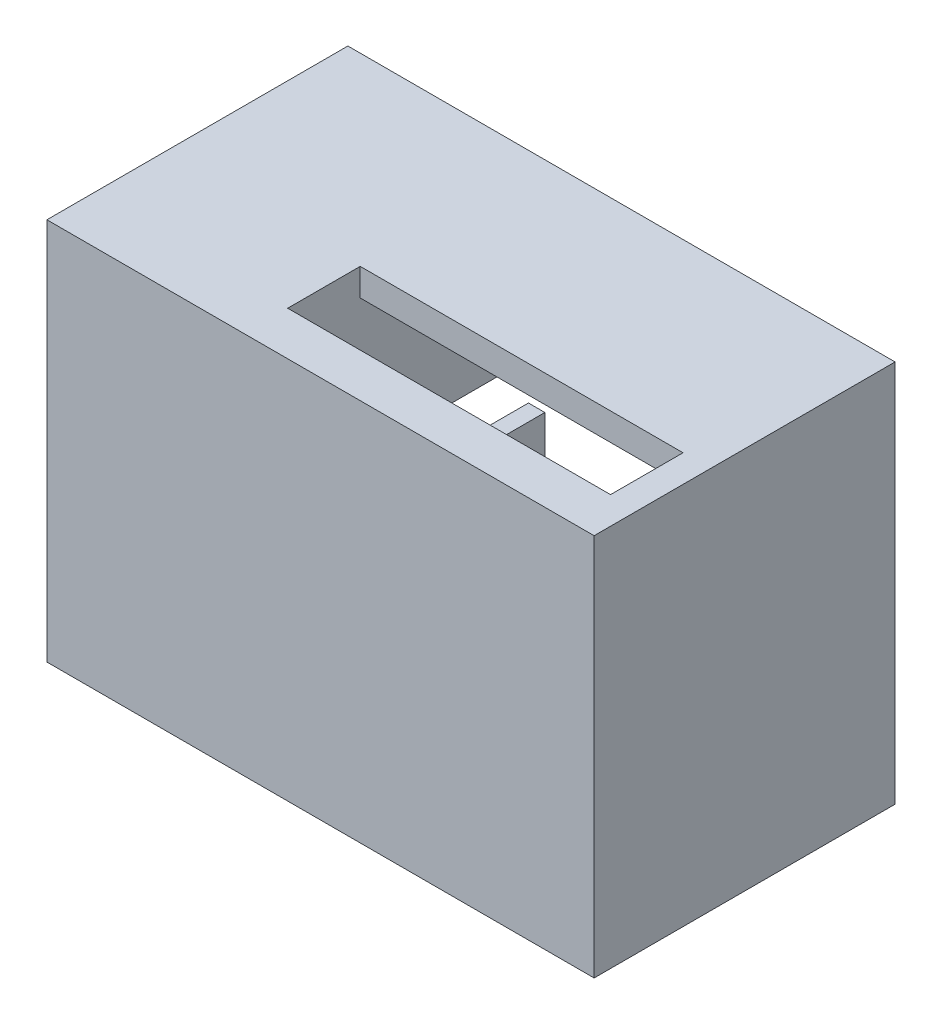
SolidWorks part; units mm, degrees
ref_plane "Front Plane" through (0, 0, 0) normal (0, 0, 1) x (1, 0, 0)
ref_plane "Top Plane" through (0, 0, 0) normal (0, 1, 0) x (1, 0, 0)
ref_plane "Right Plane" through (0, 0, 0) normal (1, 0, 0) x (0, 0, -1)
sketch "Sketch1" plane through (0, 0, 0) normal (0, 1, 0) x (1, 0, 0)
  line L1 (40.0198, -3.2673) -> (40.0198, 51.7327)
  line L2 (40.0198, 51.7327) -> (35.0198, 51.7327)
  line L3 (35.0198, 51.7327) -> (35.0198, 4.7327)
  line L4 (35.0198, 4.7327) -> (-26.9802, 4.7327)
  line L5 (-26.9802, 4.7327) -> (-26.9802, 51.7327)
  line L6 (-26.9802, 51.7327) -> (-59.9802, 51.7327)
  line L7 (-59.9802, 51.7327) -> (-59.9802, -3.2673)
  line L9 (-59.9802, -3.2673) -> (40.0198, -3.2673)
  dimension "D1" = 100
  dimension "D2" = 55
  dimension "D3" = 33
  dimension "D4" = 5
  dimension "D5" = 8
extrude "Boss-Extrude1" add sketch "Sketch1" along normal blind 60
sketch "Sketch3" plane through (-59.9802, 0, 0) normal (-1, 0, 0) x (0, 0, 1)
  line L0 (3.2673, 60) -> (3.2673, 0) construction
  line L2 (-28.8581, 44.1254) -> (-51.7327, 44.1254)
  line L3 (-51.7327, 60) -> (-51.7327, 0) construction
  line L4 (-28.8581, 15.8746) -> (-51.7327, 15.8746)
  line L5 (-51.7327, 15.8746) -> (-51.7327, 44.1254)
  arc A1 (-28.8581, 44.1254) -> (-28.8581, 15.8746) centre (-28.8581, 30) cw
  point P0 (-14.7327, 30)
  dimension "D1" = 18
extrude "Cut-Extrude1" cut sketch "Sketch3" against normal blind 40
ref_plane "Plane4" through (0, 0, -14.7327) normal (0, 0, -1) x (-1, 0, 0)
sketch "Sketch11" plane through (0, 0, -14.7327) normal (0, 0, -1) x (-1, 0, 0)
  line L0 (26.9802, 30) -> (59.9802, 30) construction
  line L1 (26.9802, 60) -> (26.9802, 0) construction
  line L2 (59.9802, 15.8746) -> (59.9802, 44.1254) construction
  line L4 (31.7302, 28.75) -> (34.2302, 28.75)
  line L5 (31.7302, 28.75) -> (31.7302, 31.25)
  line L6 (31.7302, 31.25) -> (34.2302, 31.25)
  line L7 (34.2302, 28.75) -> (34.2302, 31.25)
  line L8 (31.7302, 28.75) -> (34.2302, 31.25) construction
  line L9 (31.7302, 31.25) -> (34.2302, 28.75) construction
  point P6 (32.9802, 30)
  dimension "D1" = 2.5
  dimension "D2" = 2.5
  dimension "D3" = 6
extrude "Boss-Extrude2" add sketch "Sketch11" along normal blind 2.5
ref_plane "Plane5" through (35.0198, 0, 0) normal (-1, 0, 0) x (0, 0, 1)
sketch "Sketch14" plane through (0, 0, -4.7327) normal (0, 0, -1) x (-1, 0, 0)
  line L0 (-35.0198, 0) -> (26.9802, 0) construction
  line L1 (26.9802, 60) -> (23.9802, 60)
  line L2 (26.9802, 60) -> (26.9802, 0)
  line L3 (26.9802, 0) -> (23.9802, 0)
  line L4 (23.9802, 60) -> (23.9802, 0)
  dimension "D1" = 3
extrude "Boss-Extrude5" add sketch "Sketch14" along normal up to vertex (47 mm away)
sketch "Sketch12" plane through (35.0198, 0, 0) normal (-1, 0, 0) x (0, 0, 1)
  line L0 (-51.7327, 60) -> (-36.8581, 60) construction
  line L1 (-28.8581, 44.1254) -> (-28.8581, 15.8746) construction
  line L2 (-51.7327, 60) -> (-51.7327, 0) construction
  line L3 (-51.7327, 60) -> (-4.7327, 60) construction
  line L4 (-36.8581, 60) -> (-36.8581, 0) construction
  line L5 (-51.7327, 0) -> (-4.7327, 0) construction
  circle A0 centre (-36.8581, 35.3) radius 1.125
  circle A1 centre (-36.8581, 21.3) radius 1.125
  point P9 (0, 0)
  point P15 (-28.8581, 44.1254)
  point P22 (-36.8581, 30)
  dimension "D4" = 2.25
  dimension "D5" = 2.25
  dimension "D1" = 8
  dimension "D2" = 14
  dimension "D3" = 5.3
extrude "Boss-Extrude3" add sketch "Sketch12" along normal blind 6
sketch "Sketch13" plane through (35.0198, 0, 0) normal (-1, 0, 0) x (0, 0, 1)
  line L0 (-51.7327, 60) -> (-31.2327, 60) construction
  line L1 (-51.7327, 60) -> (-4.7327, 60) construction
  line L2 (-31.2327, 60) -> (-31.2327, 0) construction
  line L3 (-51.7327, 0) -> (-4.7327, 0) construction
  line L6 (-28.8581, 44.1254) -> (-28.8581, 15.8746) construction
  circle A0 centre (-31.2327, 37.5) radius 1.25
  circle A1 centre (-31.2327, 23.8935) radius 1.25
  point P15 (-28.8581, 44.1254)
  point P17 (-28.8581, 15.8746)
  dimension "D2" = 2.5
  dimension "D3" = 2.5
sketch "Sketch15" plane through (-26.9802, 0, 0) normal (-1, 0, 0) x (0, 0, 1)
  line L0 (-51.7327, 44.1254) -> (-51.7327, 15.8746) construction
  line L1 (-28.8581, 44.1254) -> (-28.8581, 15.8746) construction
  line L2 (-28.8581, 35) -> (-51.7327, 35)
  line L3 (-28.8581, 25) -> (-51.7327, 25)
  line L4 (-51.7327, 25) -> (-51.7327, 35)
  arc A1 (-28.8581, 35) -> (-28.8581, 25) centre (-28.8581, 30) cw
  point P15 (-28.8581, 30)
  point P17 (-28.8581, 30)
  dimension "D1" = 5
extrude "Cut-Extrude2" cut sketch "Sketch15" against normal blind 10
sketch "Sketch16" plane through (0, 0, 0) normal (0, -1, 0) x (1, 0, 0)
  line L1 (-59.9802, 3.2673) -> (40.0198, 3.2673)
  line L2 (-59.9802, 3.2673) -> (-59.9802, -51.7327)
  line L3 (-59.9802, -51.7327) -> (40.0198, -51.7327)
  line L4 (40.0198, 3.2673) -> (40.0198, -51.7327)
extrude "Boss-Extrude6" add sketch "Sketch16" along normal blind 5
ref_plane "Plane6" through (0, 34.175, 0) normal (0, -1, 0) x (-1, 0, 0)
sketch "Sketch18" plane through (0, 34.175, 0) normal (0, -1, 0) x (-1, 0, 0)
  line L0 (-35.0198, 21.8581) -> (-35.0198, 9.9658)
  line L1 (-35.0198, 9.9658) -> (-29.0198, 20.3581)
  line L4 (-35.0198, 35.7331) -> (-35.0198, 37.9831) construction
  line L5 (-29.0198, 20.3581) -> (-32.5198, 20.3581)
  line L6 (-32.5198, 20.3581) -> (-32.5198, 21.8581)
  line L7 (-32.5198, 21.8581) -> (-35.0198, 21.8581)
  point P2 (-35.0198, 36.8581)
  point P7 (0, 0)
  point P9 (0, 0)
  point P10 (0, 0)
  point P11 (0, 0)
  point P12 (-35.0198, 37.8953)
  dimension "D1" = 30
  dimension "D2" = 1.5
  dimension "D3" = 2.5
  dimension "D4" = 16.5
extrude "Boss-Extrude8" add sketch "Sketch18" along normal blind 16 from offset 2 offset against normal yes
sketch "Sketch19" plane through (35.0198, 0, 0) normal (-1, 0, 0) x (0, 0, 1)
  line L1 (-35.7331, 36.8) -> (-37.9831, 36.8)
  line L2 (-35.7331, 36.8) -> (-35.7331, 19.8)
  line L3 (-35.7331, 19.8) -> (-37.9831, 19.8)
  line L4 (-37.9831, 36.8) -> (-37.9831, 19.8)
  circle A0 centre (-36.8581, 35.3) radius 1.125 construction
  circle A1 centre (-36.8581, 21.3) radius 1.125 construction
  point P5 (0, 0)
  dimension "D1" = 1.5
  dimension "D2" = 1.5
extrude "Boss-Extrude9" add sketch "Sketch19" along normal blind 2.5
sketch "Sketch20" plane through (0, 60, 0) normal (0, 1, 0) x (1, 0, 0)
  line L1 (-59.9802, -3.2673) -> (40.0198, -3.2673)
  line L5 (40.0198, -3.2673) -> (40.0198, 51.7327) construction
  line L7 (40.0198, -3.2673) -> (40.0198, 51.7327)
  line L8 (40.0198, 51.7327) -> (-59.9802, 51.7327)
  line L9 (-59.9802, -3.2673) -> (-59.9802, 51.7327)
  line L10 (-23.9802, 51.7327) -> (-23.9802, 4.7327) construction
  line L11 (35.0198, 4.7327) -> (35.0198, 17.9835) construction
  line L12 (-23.9802, 51.7327) -> (-23.9802, 4.7327) construction
  line L13 (-23.9802, 4.7327) -> (35.0198, 4.7327)
  line L14 (35.0198, 51.7327) -> (35.0198, 31.2327) construction
  line L15 (35.0198, 4.7327) -> (35.0198, 17.9835)
  line L16 (35.0198, 51.7327) -> (35.0198, 4.7327) construction
  line L17 (35.0198, 17.9835) -> (-23.9802, 17.9835)
  line L18 (-23.9802, 17.9835) -> (-23.9802, 4.7327)
  point P1 (35.0198, 11.3581)
  point P2 (0, 0)
  dimension "D1" = 17.5
extrude "Boss-Extrude10" add sketch "Sketch20" along normal blind 5
